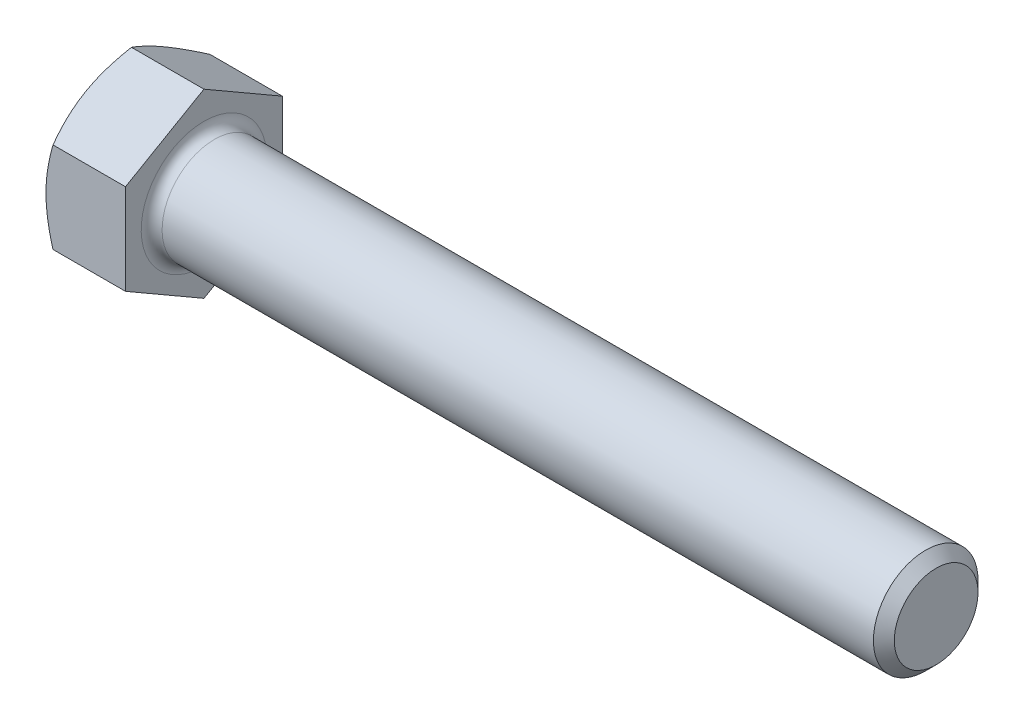
SolidWorks part; units mm, degrees
ref_plane "Front Plane" through (0, 0, 0) normal (0, 0, 1) x (1, 0, 0)
ref_plane "Top Plane" through (0, 0, 0) normal (0, 1, 0) x (1, 0, 0)
ref_plane "Right Plane" through (0, 0, 0) normal (1, 0, 0) x (0, 0, -1)
ref_plane "Plane1"
sketch "Sketch1" plane through (0, 0, 0) normal (0, 0, 1) x (1, 0, 0)
  line L0 (44.45, 0) -> (44.45, 3.175)
  line L1 (44.45, 3.175) -> (0, 3.175)
  line L2 (0, 3.175) -> (0, 0)
  line L3 (0, 0) -> (44.45, 0)
  line L4 (44.45, 0) -> (0, 0) construction
  dimension "D1" = 90
  dimension "D2" = 44.45
revolve "Body" add sketch "Sketch1" angle 360 about L4
cosmetic thread "Cosmetic Thread1" parameters "D1"=43.6702, "D2"=4.8387
sketch "Sketch2" plane through (0, 0, 0) normal (-1, 0, 0) x (0, 0, 1)
  line L0 (0, 5.4993) -> (4.7625, 2.7496)
  line L1 (4.7625, 2.7496) -> (4.7625, -2.7496)
  line L2 (4.7625, -2.7496) -> (0, -5.4993)
  line L3 (0, -5.4993) -> (-4.7625, -2.7496)
  line L4 (-4.7625, -2.7496) -> (-4.7625, 2.7496)
  line L5 (-4.7625, 2.7496) -> (0, 5.4993)
  dimension "D1" = 9.525
extrude "Head" add sketch "Sketch2" along normal blind 4.826
ref_plane "Plane2"
sketch "Sketch3" plane through (0, 0, 0) normal (0, 0, 1) x (1, 0, 0)
  line L0 (-4.826, 4.7625) -> (-4.2761, 5.715)
  line L1 (-4.2761, 5.715) -> (-4.826, 5.715)
  line L2 (-4.826, 5.715) -> (-4.826, 4.7625)
  line L3 (-1.1, 0) -> (-0.234, 0) construction
  line L5 (0, 2.7496) -> (0, 5.4993) construction
  dimension "D1" = 60
  dimension "D2" = 60
  dimension "D3" = 30
revolve "Thread" cut sketch "Sketch3" angle 360 about L3
chamfer "Chamfer2" distance 0.635 distance2 0.6351 1 edges at (44.45, 3.175, 0)
fillet "Fillet" radius 0.635 1 edges at (0, 3.175, 0)
